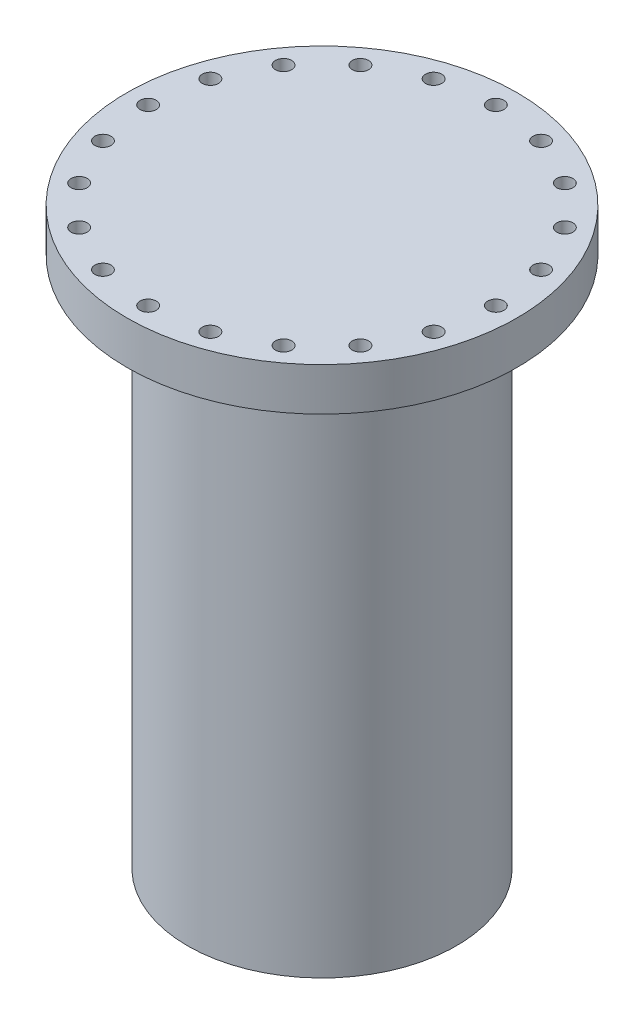
SolidWorks part; units mm, degrees
ref_plane "Front Plane" through (0, 0, 0) normal (0, 0, 1) x (1, 0, 0)
ref_plane "Top Plane" through (0, 0, 0) normal (0, 1, 0) x (1, 0, 0)
ref_plane "Right Plane" through (0, 0, 0) normal (1, 0, 0) x (0, 0, -1)
sketch "Sketch1" plane through (0, 0, 0) normal (0, 1, 0) x (1, 0, 0)
  circle A0 centre (0, 0) radius 101.6
  dimension "D1" = 203.2
extrude "Extrude1" add sketch "Sketch1" along normal blind 22.352
sketch "Sketch5" plane through (0, 0, 0) normal (0, -1, 0) x (1, 0, 0)
  circle A0 centre (0, 0) radius 70
  circle A1 centre (0, 0) radius 67.46
  dimension "D1" = 2.54
  dimension "D2" = 140
extrude "Extrude2" add sketch "Sketch5" along normal blind 276.606
sketch "Sketch6" plane through (0, 22.352, 0) normal (0, 1, 0) x (1, 0, 0)
  line L0 (0, 0) -> (0, 58.1285) construction
  circle A0 centre (0, 90.5256) radius 4.2164
  dimension "D1" = 8.4328
  dimension "D2" = 90.5256
extrude "Extrude3" cut sketch "Sketch6" against normal through all
pattern_circular "CirPattern1" count 20 over 360 about axis through (0, 0, 0) along (0, 1, 0) of "Extrude3"
